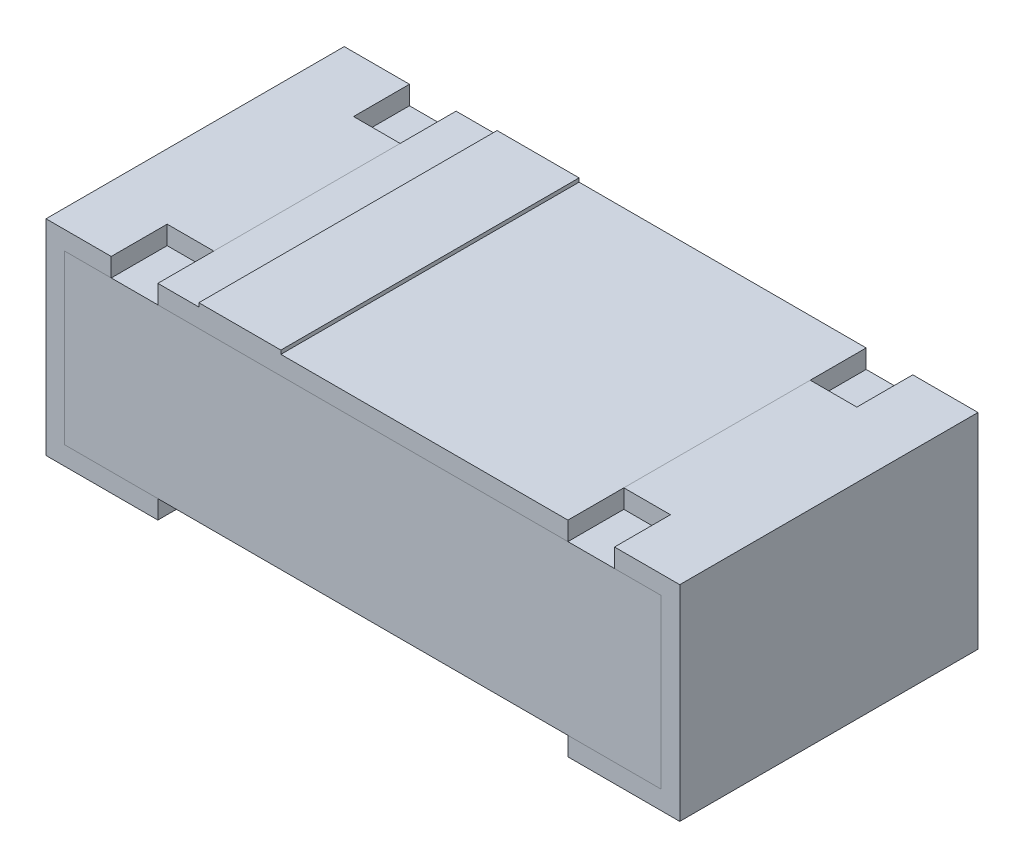
SolidWorks part; units mm, degrees
ref_plane "Front Plane" through (0, 0, 0) normal (0, 0, 1) x (1, 0, 0)
ref_plane "Top Plane" through (0, 0, 0) normal (0, 1, 0) x (1, 0, 0)
ref_plane "Right Plane" through (0, 0, 0) normal (1, 0, 0) x (0, 0, -1)
sketch "Croquis1" plane through (0, 0, 0) normal (0, 1, 0) x (1, 0, 0)
  line L1 (0.8, 0.4) -> (-0.8, 0.4)
  line L2 (0.8, 0.4) -> (0.8, -0.4)
  line L3 (0.8, -0.4) -> (-0.8, -0.4)
  line L4 (-0.8, 0.4) -> (-0.8, -0.4)
  line L5 (0.8, 0.4) -> (-0.8, -0.4) construction
  line L6 (0.8, -0.4) -> (-0.8, 0.4) construction
  point P0 (0, 0)
  dimension "D1" = 0.8
  dimension "D2" = 1.6
extrude "Extruir1" add sketch "Croquis1" along normal blind 0.5
sketch "Croquis2" plane through (0, 0, 0.4) normal (0, 0, 1) x (1, 0, 0)
  line L0 (0.8, 0.5) -> (0.8, 0) construction
  line L1 (-0.8, 0) -> (0.8, 0)
  line L2 (-0.8, 0) -> (-0.8, 0.05)
  line L3 (-0.8, 0.05) -> (0.8, 0.05)
  line L4 (0.8, 0) -> (0.8, 0.05)
  dimension "D1" = 0.05
extrude "Extruir2" cut sketch "Croquis2" against normal through all
sketch "Croquis3" plane through (0, 0, 0.4) normal (0, 0, 1) x (1, 0, 0)
  line L0 (-0.55, 0.55) -> (-0.85, 0.55)
  line L1 (-0.85, 0.55) -> (-0.85, 0)
  line L2 (-0.85, 0) -> (-0.55, 0)
  line L4 (-0.8, 0.5) -> (-0.8, 0.05) construction
  line L5 (-0.8, 0.5) -> (0.8, 0.5) construction
  dimension "D1" = 0.05
  dimension "D2" = 0.05
  dimension "D3" = 0.3
  dimension "D4" = 0.3
  dimension "D5" = 0.55
sketch3d "Croquis3D1"
  line L0 (-0.55, 0.55, 0.4) -> (-0.55, 0.55, -0.4)
  line L1 (-0.55, 0.55, -0.4) -> (-0.55, 0.5, -0.4)
  line L2 (-0.55, 0.5, -0.4) -> (-0.55, 0.5, 0.4)
  line L3 (-0.55, 0.5, 0.4) -> (-0.55, 0.55, 0.4)
  line L4 (-0.8, 0.5, -0.4) -> (-0.8, 0.5, 0.4) construction
  dimension "D1" = 0.3
sweep "Barrer1" add profiles "Croquis3D1" path "Croquis3"
ref_plane "Plano1" through (0, 0.5, 0.4) normal (1, 0, 0) x (0, 0, -1)
mirror "Simetría1" about plane through (0, 0.5, 0.4) normal (1, 0, 0) of bodies 104
sketch "Croquis4" plane through (-0.55, 0, 0) normal (1, 0, 0) x (0, 0, -1)
  line L1 (-0.4, 0.55) -> (0.4, 0.55)
  line L2 (-0.4, 0.55) -> (-0.4, 0.5)
  line L3 (-0.4, 0.5) -> (0.4, 0.5)
  line L4 (0.4, 0.55) -> (0.4, 0.5)
extrude "Extruir3" add sketch "Croquis4" along normal up to surface (1.1 mm away) separate body up to face at (0.55, 0.525, 0)
sketch "Croquis5" plane through (0, 0.55, 0) normal (0, 1, 0) x (1, 0, 0)
  line L0 (0, -0.4) -> (0, 0.4) construction
  line L1 (-0.55, -0.4) -> (-0.675, -0.4)
  line L2 (-0.55, -0.4) -> (-0.55, -0.25)
  line L3 (-0.55, -0.25) -> (-0.675, -0.25)
  line L4 (-0.675, -0.4) -> (-0.675, -0.25)
  line L5 (0.55, -0.4) -> (-0.55, -0.4) construction
  line L6 (0.55, 0.4) -> (-0.55, 0.4) construction
  line L7 (-0.55, 0) -> (0.55, 0) construction
  line L8 (-0.55, 0.4) -> (-0.55, -0.4) construction
  line L9 (0.55, 0.4) -> (0.55, -0.4) construction
  line L10 (-0.675, 0.4) -> (-0.675, 0.25)
  line L11 (-0.55, 0.25) -> (-0.675, 0.25)
  line L12 (-0.55, 0.4) -> (-0.55, 0.25)
  line L13 (-0.55, 0.4) -> (-0.675, 0.4)
  line L14 (0.55, 0.4) -> (0.675, 0.4)
  line L15 (0.55, 0.4) -> (0.55, 0.25)
  line L16 (0.55, 0.25) -> (0.675, 0.25)
  line L17 (0.675, 0.4) -> (0.675, 0.25)
  line L18 (0.675, -0.4) -> (0.675, -0.25)
  line L19 (0.55, -0.25) -> (0.675, -0.25)
  line L20 (0.55, -0.4) -> (0.55, -0.25)
  line L21 (0.55, -0.4) -> (0.675, -0.4)
  dimension "D1" = 0.15
  dimension "D2" = 0.125
extrude "Extruir4" cut sketch "Croquis5" against normal up to next (0.05 mm away)
sketch "Sketch1" plane through (0, 0.55, 0) normal (0, 1, 0) x (1, 0, 0)
  line L0 (0.55, 0.4) -> (-0.55, 0.4) construction
  line L1 (-0.44, 0.4) -> (-0.22, 0.4)
  line L2 (-0.44, 0.4) -> (-0.44, -0.4)
  line L3 (-0.44, -0.4) -> (-0.22, -0.4)
  line L4 (-0.22, 0.4) -> (-0.22, -0.4)
  line L5 (0.55, -0.4) -> (-0.55, -0.4) construction
  line L6 (-0.55, 0.4) -> (-0.55, -0.4) construction
  line L7 (0.55, 0.4) -> (0.55, -0.4) construction
  dimension "D1" = 0.11
  dimension "D2" = 0.22
  dimension "D3" = 0.77
extrude "Boss-Extrude1" add sketch "Sketch1" along normal blind 0.01
